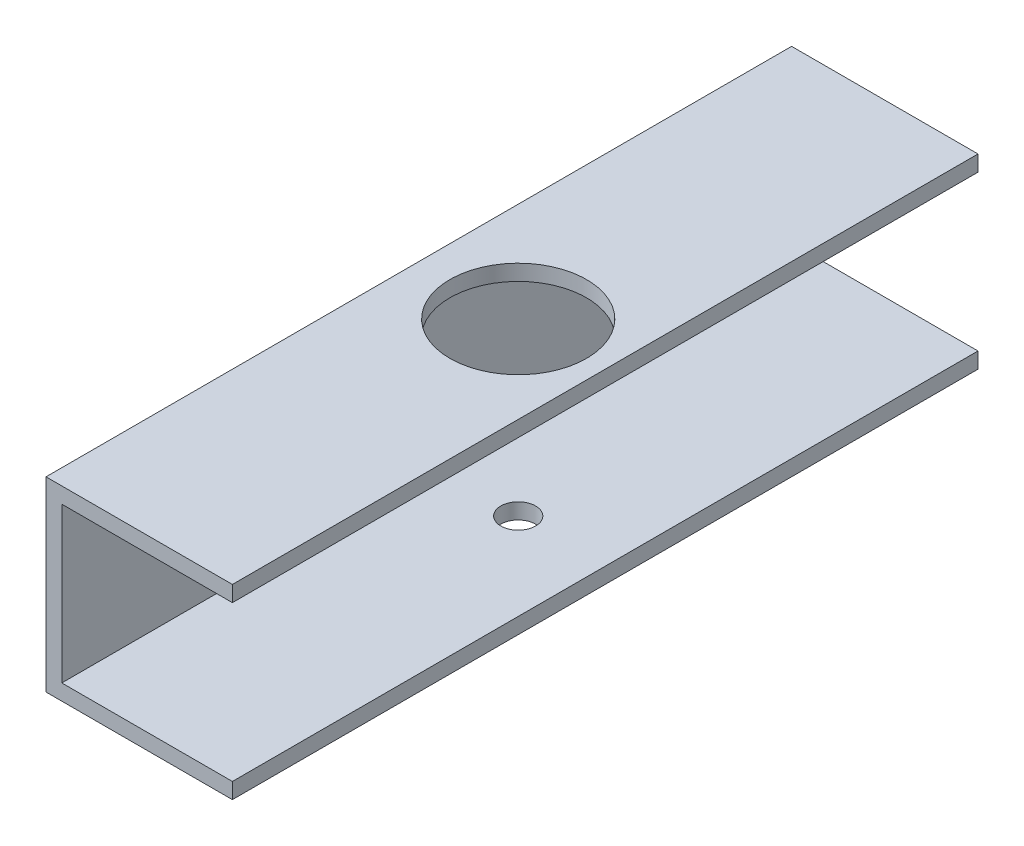
SolidWorks part; units mm, degrees
ref_plane "Front Plane" through (0, 0, 0) normal (0, 0, 1) x (1, 0, 0)
ref_plane "Top Plane" through (0, 0, 0) normal (0, 1, 0) x (1, 0, 0)
ref_plane "Right Plane" through (0, 0, 0) normal (1, 0, 0) x (0, 0, -1)
sketch "Sketch1" plane through (0, 0, 0) normal (0, 0, 1) x (1, 0, 0)
  line L0 (0, -37.5) -> (0, 37.5)
  line L1 (0, 37.5) -> (75, 37.5)
  line L2 (75, 37.5) -> (75, 31.15)
  line L3 (75, 31.15) -> (6.35, 31.15)
  line L4 (6.35, 31.15) -> (6.35, -31.15)
  line L5 (6.35, -31.15) -> (75, -31.15)
  line L6 (75, -31.15) -> (75, -37.5)
  line L7 (75, -37.5) -> (0, -37.5)
  line L8 (0, 0) -> (6.35, 0) construction
  dimension "D1" = 75
  dimension "D2" = 75
  dimension "D3" = 6.35
extrude "Boss-Extrude1" add sketch "Sketch1" along normal blind 300
sketch "Sketch2" plane through (0, 37.5, 0) normal (0, 1, 0) x (1, 0, 0)
  line L0 (40, -150) -> (0, -150) construction
  line L1 (0, -300) -> (0, 0) construction
  circle A0 centre (40, -150) radius 27.5
  dimension "D2" = 55
  dimension "D1" = 40
extrude "Cut-Extrude1" cut sketch "Sketch2" against normal blind 10
sketch "Sketch3" plane through (0, -37.5, 0) normal (0, -1, 0) x (1, 0, 0)
  circle A0 centre (40, 150) radius 7
  circle A1 centre (40, 150) radius 27.5 construction
  dimension "D1" = 14
extrude "Cut-Extrude2" cut sketch "Sketch3" against normal blind 10
